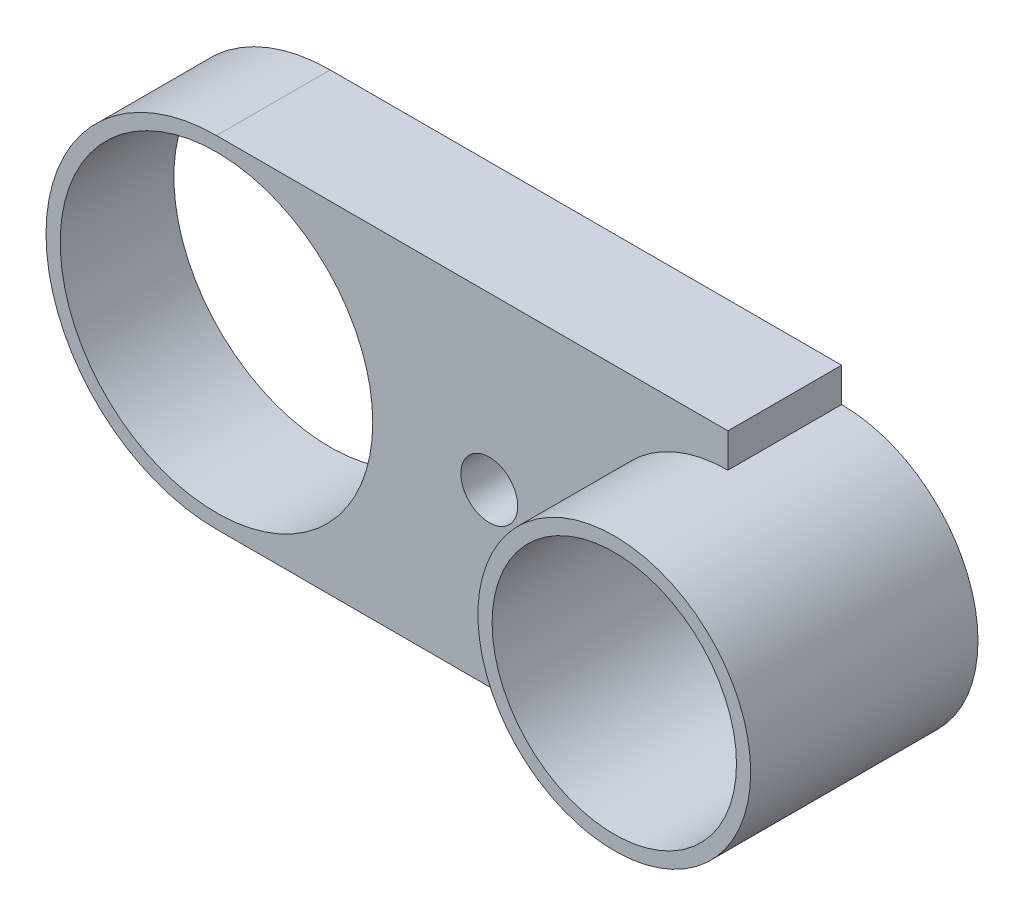
SolidWorks part; units mm, degrees
ref_plane "Front Plane" through (0, 0, 0) normal (0, 0, 1) x (1, 0, 0)
ref_plane "Top Plane" through (0, 0, 0) normal (0, 1, 0) x (1, 0, 0)
ref_plane "Right Plane" through (0, 0, 0) normal (1, 0, 0) x (0, 0, -1)
sketch "Sketch1" plane through (0, 0, 0) normal (0, 0, 1) x (1, 0, 0)
  circle A0 centre (0, 0) radius 30
  dimension "D1" = 60
extrude "Boss-Extrude1" add sketch "Sketch1" along normal blind 20
sketch "Sketch2" plane through (0, 0, 20) normal (0, 0, 1) x (1, 0, 0)
  circle A0 centre (0, 0) radius 27.5
  dimension "D1" = 55
extrude "Cut-Extrude1" cut sketch "Sketch2" against normal through all
ref_plane "Plane1" through (0, 0, 20) normal (0, 0, 1) x (1, 0, 0)
sketch "Sketch4" plane through (0, 0, 20) normal (0, 0, 1) x (1, 0, 0)
  line L0 (0, 30) -> (90, 30)
  line L1 (90, 30) -> (90, 24)
  line L2 (0, -30) -> (90, -30)
  line L3 (90, -30) -> (90, -24)
  arc A0 (90, -24) -> (90, 24) centre (90, 0) ccw
  circle A1 centre (0, 0) radius 30 construction
  arc A2 (0, -30) -> (0, 30) centre (0, 0) ccw
  dimension "D1" = 48
  dimension "D2" = 90
extrude "Boss-Extrude2" add sketch "Sketch4" against normal blind 20
sketch "Sketch6" plane through (0, 0, 20) normal (0, 0, 1) x (1, 0, 0)
  circle A0 centre (90, 0) radius 21.5
  dimension "D1" = 43
extrude "Cut-Extrude2" cut sketch "Sketch6" against normal blind 35
sketch "Sketch10" plane through (0, 0, 20) normal (0, 0, 1) x (1, 0, 0)
  circle A0 centre (48, 0) radius 5
  dimension "D1" = 10
  dimension "D2" = 48
extrude "Cut-Extrude5" cut sketch "Sketch10" against normal through all
sketch "Sketch11" plane through (0, 0, 20) normal (0, 0, 1) x (1, 0, 0)
  circle A0 centre (90, 0) radius 24
extrude "Boss-Extrude3" add sketch "Sketch11" along normal blind 20
sketch "Sketch12" plane through (0, 0, 40) normal (0, 0, 1) x (1, 0, 0)
  circle A0 centre (90, 0) radius 24
extrude "Boss-Extrude4" add sketch "Sketch12" against normal blind 40
sketch "Sketch13" plane through (0, 0, 40) normal (0, 0, 1) x (1, 0, 0)
  circle A0 centre (90, 0) radius 21.5
  circle A1 centre (90, 0) radius 24 construction
  dimension "D1" = 0
extrude "Cut-Extrude6" cut sketch "Sketch13" against normal blind 35
